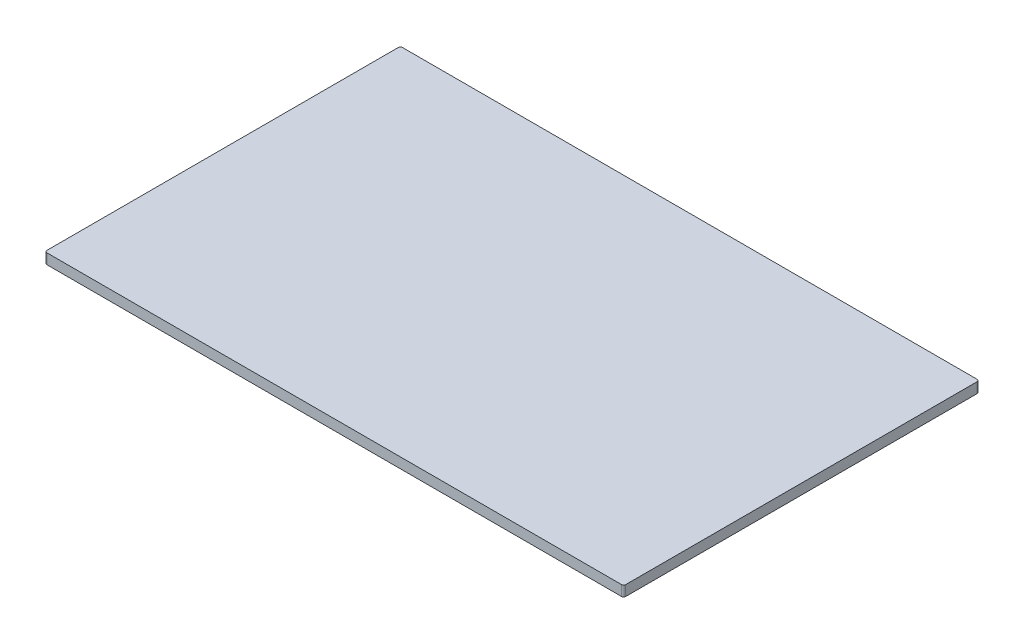
SolidWorks part; units mm, degrees
ref_plane "Front Plane" through (0, 0, 0) normal (0, 0, 1) x (1, 0, 0)
ref_plane "Top Plane" through (0, 0, 0) normal (0, 1, 0) x (1, 0, 0)
ref_plane "Right Plane" through (0, 0, 0) normal (1, 0, 0) x (0, 0, -1)
sketch "Sketch1" plane through (0, 0, 0) normal (0, 1, 0) x (1, 0, 0)
  line L1 (280, -172) -> (-280, -172)
  line L2 (280, -172) -> (280, 172)
  line L3 (280, 172) -> (-280, 172)
  line L4 (-280, -172) -> (-280, 172)
  line L5 (280, -172) -> (-280, 172) construction
  line L6 (280, 172) -> (-280, -172) construction
  point P0 (0, 0)
  dimension "D1" = 560
  dimension "D2" = 344
extrude "Boss-Extrude1" add sketch "Sketch1" along normal blind 10
fillet "Fillet1" radius 2 4 edges at (280, 5, -172) (280, 5, 172) (-280, 5, 172) (-280, 5, -172)
